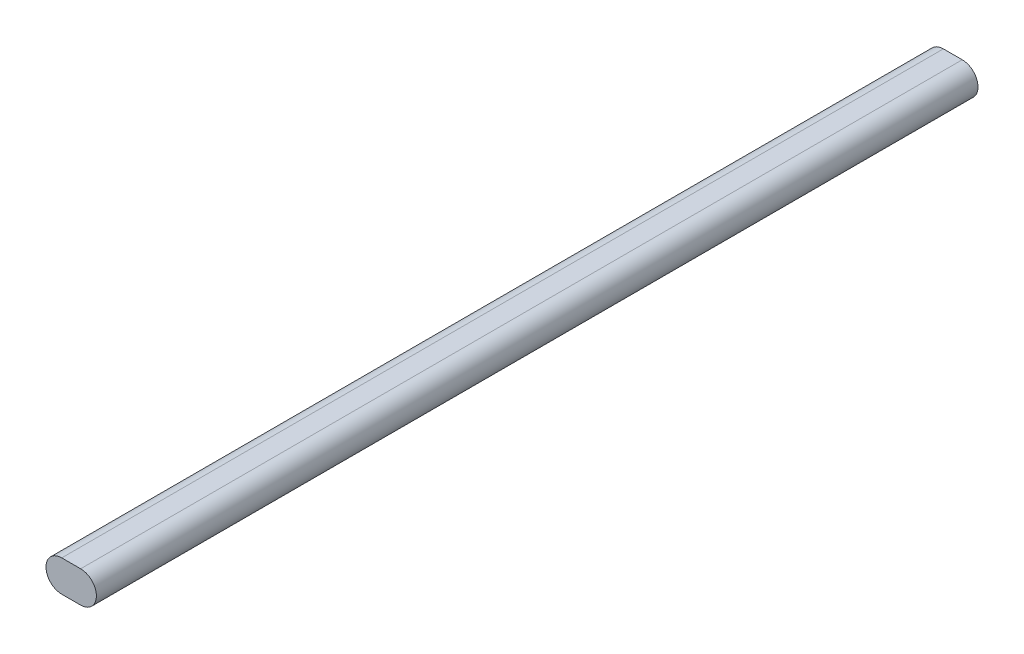
SolidWorks part; units mm, degrees
ref_plane "Front Plane" through (0, 0, 0) normal (0, 0, 1) x (1, 0, 0)
ref_plane "Top Plane" through (0, 0, 0) normal (0, 1, 0) x (1, 0, 0)
ref_plane "Right Plane" through (0, 0, 0) normal (1, 0, 0) x (0, 0, -1)
sketch "Sketch1" plane through (0, 0, 0) normal (0, 0, 1) x (1, 0, 0)
  line L0 (-20, 0) -> (-7.5, 0) construction
  line L1 (20, -12.5) -> (-20, -12.5)
  line L2 (20, -12.5) -> (20, 12.5)
  line L3 (20, 12.5) -> (-20, 12.5)
  line L4 (-20, -12.5) -> (-20, 12.5)
  line L5 (20, -12.5) -> (-20, 12.5) construction
  line L6 (20, 12.5) -> (-20, -12.5) construction
  line L7 (20, 0) -> (7.5, 0) construction
  circle A0 centre (-7.5, 0) radius 12.5
  circle A1 centre (7.5, 0) radius 12.5
  point P0 (0, 0)
  dimension "D1" = 40
  dimension "D2" = 25
  dimension "D3" = 12.5
  dimension "D4" = 12.5
extrude "Boss-Extrude1" add sketch "Sketch1" along normal blind 700 contours A1 A0 | A0 A1 | A1 L3 A0 | A1 A0 L1 | A1 A0
